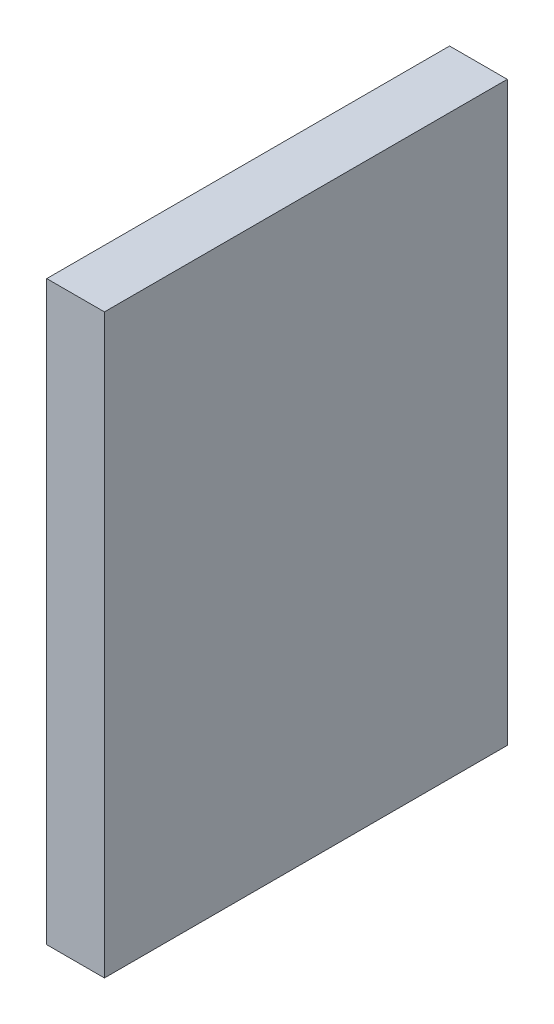
SolidWorks part; units mm, degrees
material "Acrylic (Medium-high impact)"
ref_plane "Front Plane" through (0, 0, 0) normal (0, 0, 1) x (1, 0, 0)
ref_plane "Top Plane" through (0, 0, 0) normal (0, 1, 0) x (1, 0, 0)
ref_plane "Right Plane" through (0, 0, 0) normal (1, 0, 0) x (0, 0, -1)
sketch "Sketch1" plane through (0, 0, 0) normal (1, 0, 0) x (0, 0, -1)
  line L1 (0, 0) -> (20.95, 0)
  line L2 (0, 0) -> (0, 30)
  line L3 (0, 30) -> (20.95, 30)
  line L4 (20.95, 0) -> (20.95, 30)
  dimension "D1" = 30
  dimension "D2" = 20.95
extrude "Boss-Extrude1" add sketch "Sketch1" along normal blind 3
